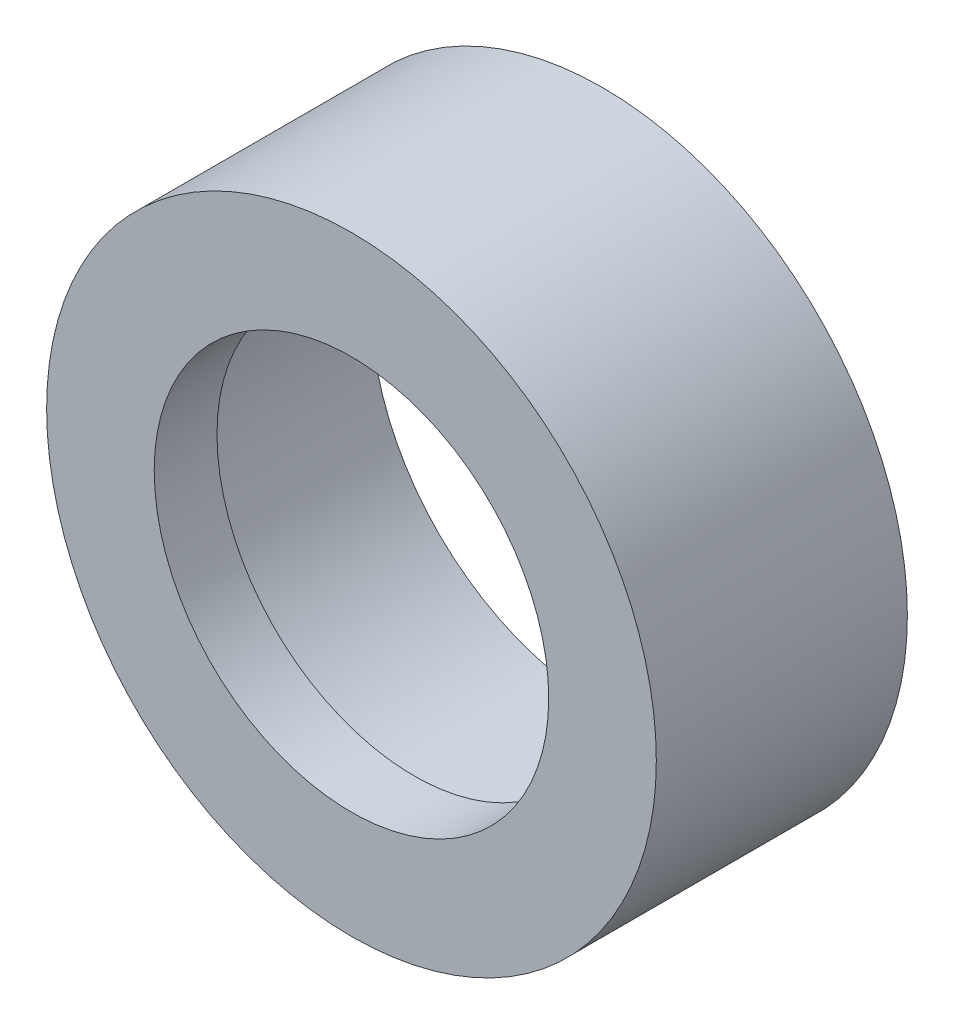
SolidWorks part; units mm, degrees
material "Alumina"
ref_plane "Front Plane" through (0, 0, 0) normal (0, 0, 1) x (1, 0, 0)
ref_plane "Top Plane" through (0, 0, 0) normal (0, 1, 0) x (1, 0, 0)
ref_plane "Right Plane" through (0, 0, 0) normal (1, 0, 0) x (0, 0, -1)
sketch "Sketch1" plane through (0, 0, 0) normal (0, 0, 1) x (1, 0, 0)
  circle A0 centre (0, 0) radius 17
  dimension "D1" = 34
extrude "Boss-Extrude1" add sketch "Sketch1" along normal blind 14
sketch "Sketch2" plane through (0, 0, 0) normal (0, 0, 1) x (1, 0, 0)
  circle A0 centre (0, 0) radius 12.9
  dimension "D1" = 25.8
extrude "Cut-Extrude1" cut sketch "Sketch2" along normal blind 10.5
sketch "Sketch3" plane through (0, 0, 0) normal (0, 0, 1) x (1, 0, 0)
  circle A0 centre (0, 0) radius 11
  dimension "D1" = 22
extrude "Cut-Extrude3" cut sketch "Sketch3" along normal through all
